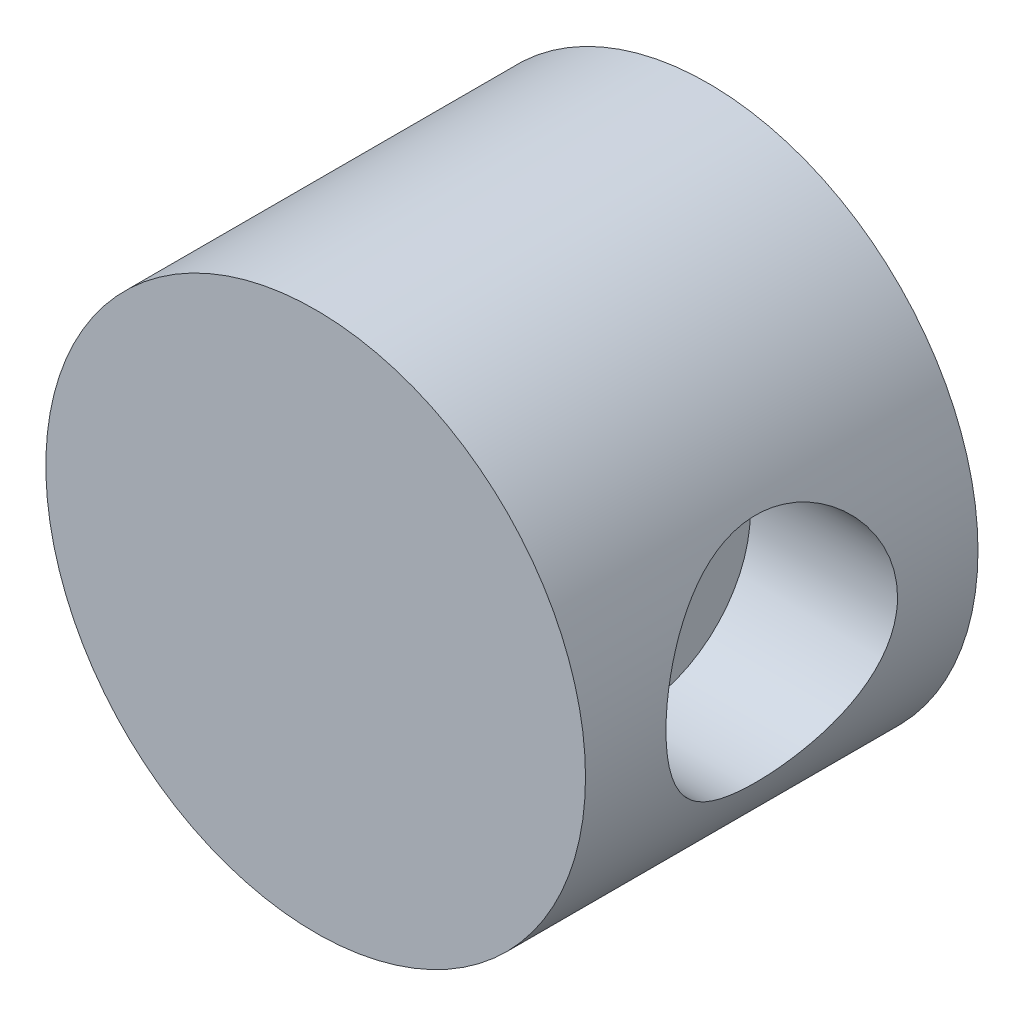
SolidWorks part; units mm, degrees
ref_plane "Alzado" through (0, 0, 0) normal (0, 0, 1) x (1, 0, 0)
ref_plane "Planta" through (0, 0, 0) normal (0, 1, 0) x (1, 0, 0)
ref_plane "Vista lateral" through (0, 0, 0) normal (1, 0, 0) x (0, 0, -1)
sketch "Croquis1" plane through (0, 0, 0) normal (0, 0, 1) x (1, 0, 0)
  circle A0 centre (0, 0) radius 27.5
  dimension "D1" = 55
extrude "Saliente-Extruir1" add sketch "Croquis1" along normal blind 40
ref_plane "Plano1" through (-27.5, 0, 0) normal (-1, 0, 0) x (0, 0, 1)
sketch "Croquis2" plane through (-27.5, 0, 0) normal (-1, 0, 0) x (0, 0, 1)
  line L0 (0, 0) -> (40, 0) construction
  line L1 (0, 27.5) -> (0, -27.5) construction
  line L2 (40, -27.5) -> (40, 27.5) construction
  circle A0 centre (20, 0) radius 11.8005
extrude "Cortar-Extruir1" cut sketch "Croquis2" against normal blind 15
ref_plane "Plano2" through (27.5, 0, 0) normal (-1, 0, 0) x (0, 0, 1)
sketch "Croquis3" plane through (27.5, 0, 0) normal (-1, 0, 0) x (0, 0, 1)
  circle A0 centre (20, 0) radius 11.8005
extrude "Cortar-Extruir4" cut sketch "Croquis3" along normal blind 15
